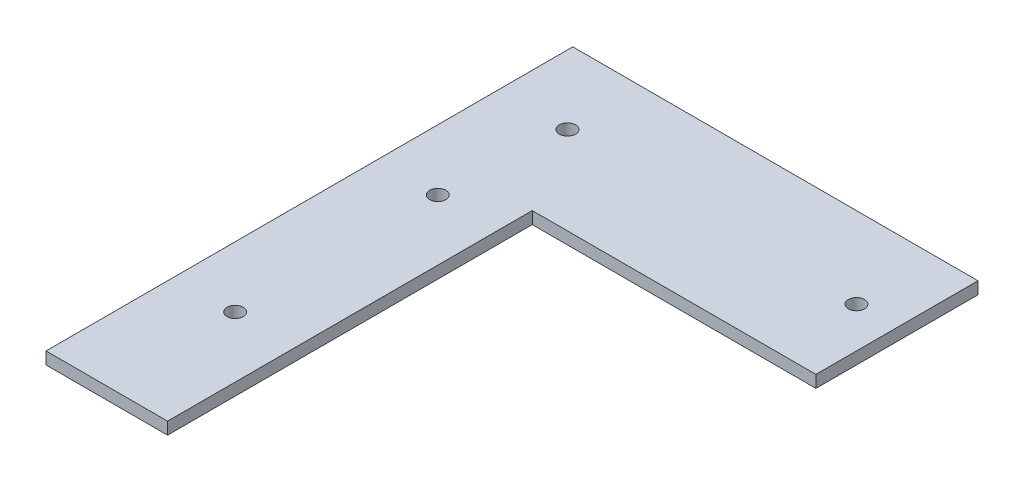
SolidWorks part; units mm, degrees
ref_plane "Alzado" through (0, 0, 0) normal (0, 0, 1) x (1, 0, 0)
ref_plane "Planta" through (0, 0, 0) normal (0, 1, 0) x (1, 0, 0)
ref_plane "Vista lateral" through (0, 0, 0) normal (1, 0, 0) x (0, 0, -1)
sketch "Croquis1" plane through (0, 0, 0) normal (0, 1, 0) x (1, 0, 0)
  line L0 (-22.4355, -36.6762) -> (-52.4355, -36.6762)
  line L1 (-52.4355, -36.6762) -> (-52.4355, 93.3238)
  line L2 (-52.4355, 93.3238) -> (47.5645, 93.3238)
  line L3 (47.5645, 93.3238) -> (47.5645, 53.3238)
  line L4 (47.5645, 53.3238) -> (-22.4355, 53.3238)
  line L5 (-22.4355, 53.3238) -> (-22.4355, -36.6762)
  dimension "D1" = 100
  dimension "D2" = 130
  dimension "D3" = 40
  dimension "D4" = 30
extrude "Saliente-Extruir1" add sketch "Croquis1" along normal blind 3
sketch "Croquis2" plane through (0, 3, 0) normal (0, 1, 0) x (1, 0, 0)
  line L0 (47.5645, 93.3238) -> (-52.4355, 93.3238) construction
  line L2 (47.5645, 53.3238) -> (47.5645, 93.3238) construction
  line L3 (-52.4355, 93.3238) -> (-52.4355, -36.6762) construction
  circle A0 centre (37.5645, 73.3238) radius 2
  circle A1 centre (-35.4355, 75.0027) radius 2
  circle A2 centre (-37.4355, 45.0027) radius 2
  circle A3 centre (-37.4355, -4.9973) radius 2
  point P12 (25.9655, 71.3238)
  point P13 (0, 0)
  point P16 (0, 0)
  dimension "D1" = 4
  dimension "D2" = 4
  dimension "D3" = 4
  dimension "D4" = 4
  dimension "D7" = 73
  dimension "D8" = 30
  dimension "D9" = 50
  dimension "D10" = 15
  dimension "D11" = 15
  dimension "D5" = 20
  dimension "D6" = 10
extrude "Saliente-Extruir2" add sketch "Croquis2" against normal through all
sketch "Croquis3" plane through (0, 3, 0) normal (0, 1, 0) x (1, 0, 0)
  circle A1 centre (37.5645, 73.3238) radius 2
  circle A2 centre (-37.4355, 45.0027) radius 2
  circle A3 centre (-37.4355, -4.9973) radius 2
  circle A4 centre (-35.4355, 75.0027) radius 2
extrude "Cortar-Extruir1" cut sketch "Croquis3" against normal through all
